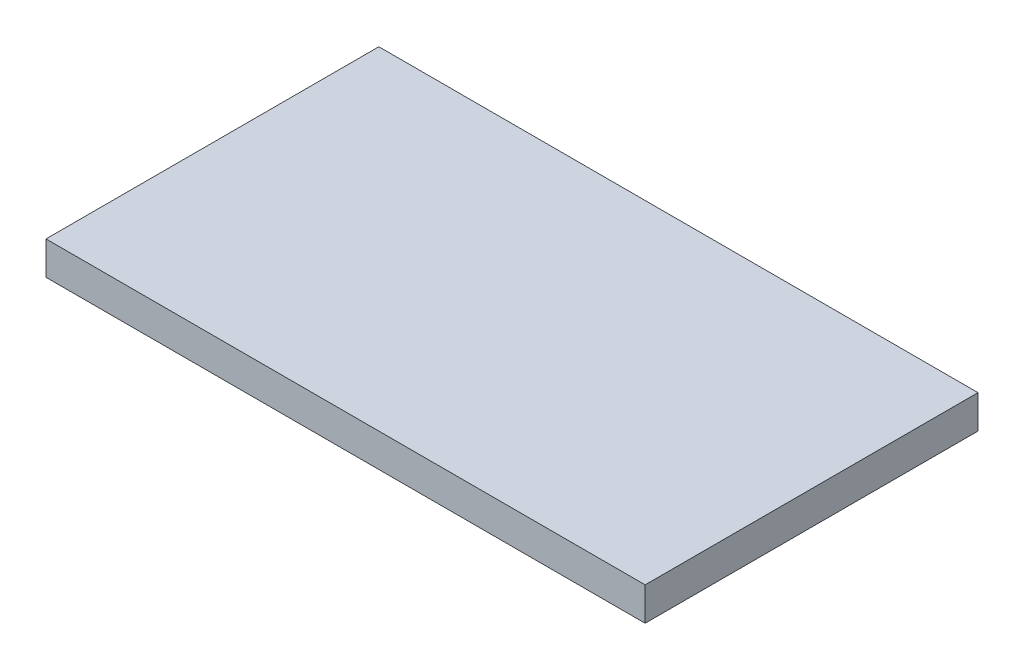
SolidWorks part; units mm, degrees
ref_plane "Front Plane" through (0, 0, 0) normal (0, 0, 1) x (1, 0, 0)
ref_plane "Top Plane" through (0, 0, 0) normal (0, 1, 0) x (1, 0, 0)
ref_plane "Right Plane" through (0, 0, 0) normal (1, 0, 0) x (0, 0, -1)
sketch "Sketch1" plane through (0, 0, 0) normal (0, 1, 0) x (1, 0, 0)
  line L0 (-47.625, 0) -> (47.625, 0) construction
  line L1 (-47.625, 7.9375) -> (47.625, 7.9375)
  line L2 (-47.625, -7.9375) -> (47.625, -7.9375)
  arc A0 (-47.625, 7.9375) -> (-47.625, -7.9375) centre (-47.625, 0) ccw
  arc A1 (47.625, -7.9375) -> (47.625, 7.9375) centre (47.625, 0) ccw
  point P3 (0, 0)
  dimension "D1" = 7.9375
  dimension "D2" = 95.25
extrude "Boss-Extrude1" add sketch "Sketch1" along normal blind 1.5875
sketch "Sketch2" plane through (0, 1.5875, 0) normal (0, 1, 0) x (1, 0, 0)
  line L0 (47.625, 7.9375) -> (-47.625, 7.9375) construction
  line L1 (-14.2875, 7.9375) -> (14.2875, 7.9375)
  line L2 (-14.2875, 7.9375) -> (-14.2875, -7.9375)
  line L3 (-14.2875, -7.9375) -> (14.2875, -7.9375)
  line L4 (14.2875, 7.9375) -> (14.2875, -7.9375)
  line L5 (-47.625, -7.9375) -> (47.625, -7.9375) construction
  line L7 (-82.75, 29.0204) -> (82.8787, 29.0204)
  line L8 (-82.75, 29.0204) -> (-82.75, -28.2482)
  line L9 (-82.75, -28.2482) -> (82.8787, -28.2482)
  line L10 (82.8787, 29.0204) -> (82.8787, -28.2482)
  dimension "D1" = 14.2875
  dimension "D2" = 28.575
extrude "Cut-Extrude1" cut sketch "Sketch2" against normal blind 2.54
